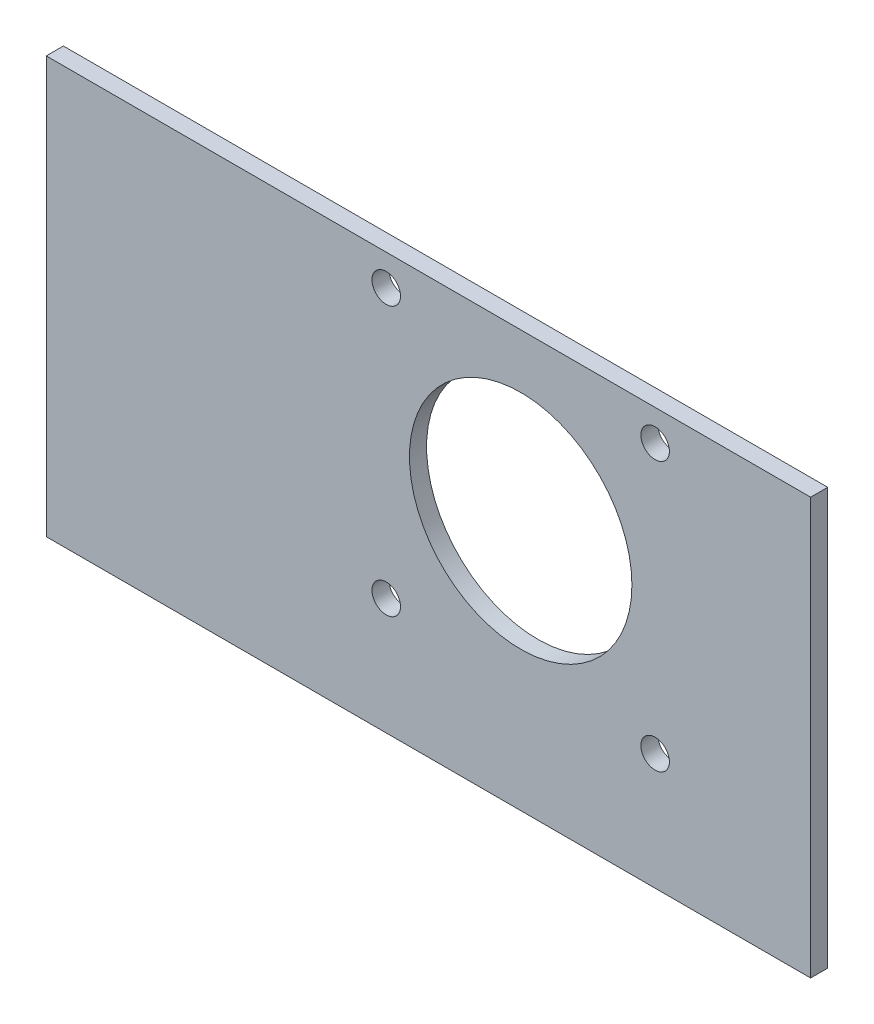
SolidWorks part; units mm, degrees
material "5052-H32"
ref_plane "Front Plane" through (0, 0, 0) normal (0, 0, 1) x (1, 0, 0)
ref_plane "Top Plane" through (0, 0, 0) normal (0, 1, 0) x (1, 0, 0)
ref_plane "Right Plane" through (0, 0, 0) normal (1, 0, 0) x (0, 0, -1)
sketch "Sketch1" plane through (0, 0, 0) normal (0, 0, 1) x (1, 0, 0)
  line L0 (59.5998, 20.43) -> (106.7398, 20.43) construction
  line L1 (0, 0) -> (134, 0)
  line L2 (0, 0) -> (0, 73)
  line L3 (0, 73) -> (134, 73)
  line L4 (134, 0) -> (134, 73)
  line L6 (59.5998, 20.43) -> (106.7398, 20.43) construction
  line L7 (59.5998, 20.43) -> (59.5998, 67.57) construction
  line L8 (59.5998, 67.57) -> (106.7398, 67.57) construction
  line L9 (106.7398, 20.43) -> (106.7398, 67.57) construction
  circle A0 centre (59.5998, 20.43) radius 2.5
  circle A1 centre (106.7398, 20.43) radius 2.5
  circle A2 centre (59.5998, 67.57) radius 2.5
  circle A3 centre (106.7398, 67.57) radius 2.5
  circle A4 centre (83.1698, 44) radius 19.5
  dimension "D3" = 5
  dimension "D4" = 39
  dimension "D1" = 134
  dimension "D2" = 73
extrude "Boss-Extrude1" add sketch "Sketch1" along normal blind 3
sketch "Sketch2" plane through (0, 0, 3) normal (0, 0, 1) x (1, 0, 0)
  line L0 (0, 73) -> (134, 73)
  line L1 (0, 73) -> (134, 73)
  line L2 (134, 73) -> (134, 0)
  line L3 (134, 73) -> (134, 0)
  line L4 (134, 0) -> (0, 0)
  line L5 (134, 0) -> (0, 0)
  line L6 (0, 0) -> (0, 73)
  line L7 (0, 0) -> (0, 73)
  circle A0 centre (106.7398, 67.57) radius 2.5
  circle A1 centre (106.7398, 67.57) radius 2.5
  circle A2 centre (83.1698, 44) radius 19.5
  circle A3 centre (83.1698, 44) radius 19.5
  circle A4 centre (59.5998, 67.57) radius 2.5
  circle A5 centre (59.5998, 67.57) radius 2.5
  circle A6 centre (59.5998, 20.43) radius 2.5
  circle A7 centre (59.5998, 20.43) radius 2.5
  circle A8 centre (106.7398, 20.43) radius 2.5
  circle A9 centre (106.7398, 20.43) radius 2.5
